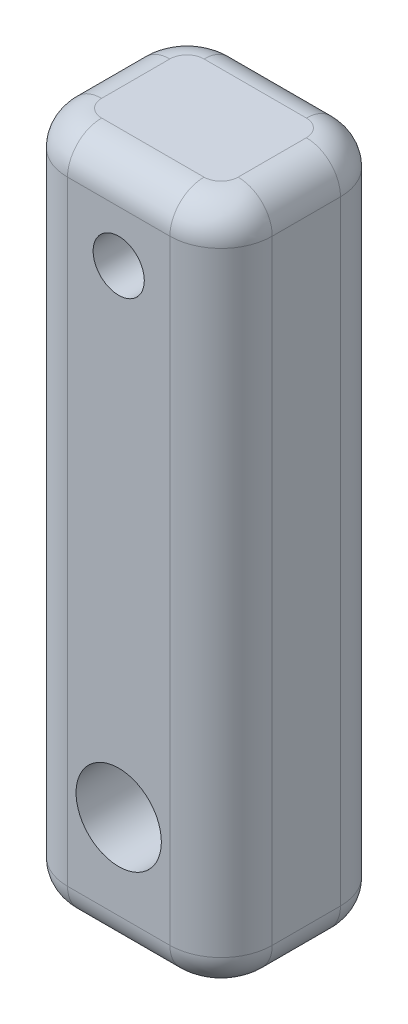
SolidWorks part; units mm, degrees
ref_plane "Front Plane" through (0, 0, 0) normal (0, 0, 1) x (1, 0, 0)
ref_plane "Top Plane" through (0, 0, 0) normal (0, 1, 0) x (1, 0, 0)
ref_plane "Right Plane" through (0, 0, 0) normal (1, 0, 0) x (0, 0, -1)
sketch "Sketch1" plane through (0, 0, 0) normal (0, 1, 0) x (1, 0, 0)
  line L1 (-7.62, 12.7) -> (7.62, 12.7)
  line L2 (-15.24, 5.08) -> (-15.24, -5.08)
  line L3 (-7.62, -12.7) -> (7.62, -12.7)
  line L4 (15.24, 5.08) -> (15.24, -5.08)
  line L5 (-15.24, 12.7) -> (15.24, -12.7) construction
  line L6 (-15.24, -12.7) -> (15.24, 12.7) construction
  arc A0 (-15.24, -5.08) -> (-7.62, -12.7) centre (-7.62, -5.08) ccw
  arc A1 (-7.62, 12.7) -> (-15.24, 5.08) centre (-7.62, 5.08) ccw
  arc A2 (7.62, 12.7) -> (15.24, 5.08) centre (7.62, 5.08) cw
  arc A3 (7.62, -12.7) -> (15.24, -5.08) centre (7.62, -5.08) ccw
  point P0 (0, 0)
  dimension "D3" = 7.62
  dimension "D1" = 30.48
  dimension "D2" = 25.4
extrude "Boss-Extrude1" add sketch "Sketch1" along normal blind 101.6
ref_plane "Plane1" through (0, 0, 12.7) normal (0, 0, 1) x (1, 0, 0)
sketch "Sketch2" plane through (0, 0, 12.7) normal (0, 0, 1) x (1, 0, 0)
  line L0 (0, 24.13) -> (0, 11.43) construction
  line L1 (-7.62, 0) -> (7.62, 0) construction
  circle A0 centre (0, 17.78) radius 6.35
  point P6 (0, 0)
  dimension "D1" = 12.7
  dimension "D2" = 17.78
extrude "Cut-Extrude1" cut sketch "Sketch2" against normal through all
sketch "Sketch3" plane through (0, 0, 12.7) normal (0, 0, 1) x (1, 0, 0)
  line L0 (-7.62, 101.6) -> (7.62, 101.6) construction
  circle A0 centre (0, 88.9) radius 3.81
  point P5 (0, 101.6)
  dimension "D1" = 7.62
  dimension "D2" = 12.7
extrude "Cut-Extrude2" cut sketch "Sketch3" against normal through all contours A0
fillet "Fillet1" radius 5.08 8 edges at (-13.0082, 0, 10.4682) (0, 0, 12.7) (13.0082, 0, 10.4682) (15.24, 0, 0) (-15.24, 0, 0) (-13.0082, 0, -10.4682) (0, 0, -12.7) (13.0082, 0, -10.4682)
fillet "Fillet2" radius 5.08 8 edges at (-15.24, 101.6, 0) (-13.0082, 101.6, -10.4682) (0, 101.6, -12.7) (13.0082, 101.6, -10.4682) (15.24, 101.6, 0) (13.0082, 101.6, 10.4682) (0, 101.6, 12.7) (-13.0082, 101.6, 10.4682)
